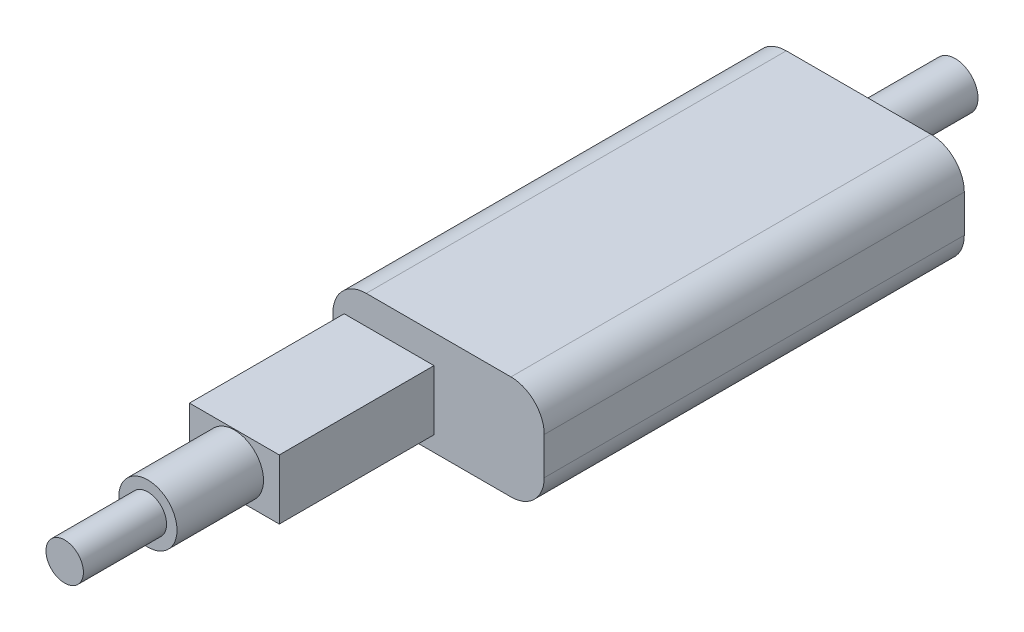
SolidWorks part; units mm, degrees
ref_plane "Plan de face" through (0, 0, 0) normal (0, 0, 1) x (1, 0, 0)
ref_plane "Plan de dessus" through (0, 0, 0) normal (0, 1, 0) x (1, 0, 0)
ref_plane "Plan de droite" through (0, 0, 0) normal (1, 0, 0) x (0, 0, -1)
sketch "Esquisse1" plane through (0, 0, 0) normal (0, 0, 1) x (1, 0, 0)
  line L1 (-12.7, 6.25) -> (12.7, 6.25)
  line L2 (-12.7, 6.25) -> (-12.7, -6.25)
  line L3 (-12.7, -6.25) -> (12.7, -6.25)
  line L4 (12.7, 6.25) -> (12.7, -6.25)
  point P4 (0, 6.25)
  point P6 (-12.7, 0)
  dimension "D1" = 25.4
  dimension "D2" = 12.5
extrude "Boss.-Extru.1" add sketch "Esquisse1" along normal mid plane 50.5
fillet "Congé1" radius 4 4 edges at (-12.7, -6.25, 0) (12.7, -6.25, 0) (12.7, 6.25, 0) (-12.7, 6.25, 0)
sketch "Esquisse2" plane through (0, 0, 25.25) normal (0, 0, 1) x (1, 0, 0)
  line L0 (-8.7, -6.25) -> (8.7, -6.25) construction
  line L1 (-7.9, 1.65) -> (-1, 1.65)
  line L2 (-7.9, 1.65) -> (-7.9, -0.25)
  line L3 (-7.9, -0.25) -> (-1, -0.25)
  line L4 (-1, 1.65) -> (-1, -0.25)
  line L5 (-12.7, 2.25) -> (-12.7, -2.25) construction
  dimension "D1" = 6.9
  dimension "D2" = 1.9
  dimension "D3" = 6
  dimension "D4" = 4.8
extrude "Boss.-Extru.2" add sketch "Esquisse2" along normal blind 1.5
sketch "Esquisse3" plane through (0, 0, 26.75) normal (0, 0, 1) x (1, 0, 0)
  line L0 (-1, 1.65) -> (-7.9, 1.65) construction
  line L1 (-9.85, 4.3) -> (0.95, 4.3)
  line L2 (-9.85, 4.3) -> (-9.85, -2.9)
  line L3 (-9.85, -2.9) -> (0.95, -2.9)
  line L4 (0.95, 4.3) -> (0.95, -2.9)
  line L5 (-7.9, 1.65) -> (-7.9, -0.25) construction
  point P6 (-4.45, 1.65)
  point P7 (-4.45, 4.3)
  point P10 (-7.9, 0.7)
  point P11 (-9.85, 0.7)
  dimension "D1" = 10.8
  dimension "D2" = 7.2
extrude "Boss.-Extru.3" add sketch "Esquisse3" along normal blind 18.6
sketch "Esquisse4" plane through (0, 0, 45.35) normal (0, 0, 1) x (1, 0, 0)
  line L0 (0.95, 4.3) -> (-9.85, 4.3) construction
  line L1 (-9.85, 4.3) -> (-9.85, -2.9) construction
  circle A0 centre (-4.45, 0.7) radius 3.5
  point P2 (0, 0)
  point P5 (-4.45, 4.3)
  point P8 (-9.85, 0.7)
  dimension "D1" = 7
extrude "Boss.-Extru.4" add sketch "Esquisse4" along normal blind 10.4
sketch "Esquisse5" plane through (0, 0, 55.75) normal (0, 0, 1) x (1, 0, 0)
  circle A0 centre (-4.45, 0.7) radius 2.25
  dimension "D1" = 4.5
extrude "Boss.-Extru.5" add sketch "Esquisse5" along normal blind 10
sketch "Esquisse7" plane through (0, 0, -25.25) normal (0, 0, -1) x (-1, 0, 0)
  line L0 (-8.7, 6.25) -> (8.7, 6.25) construction
  line L1 (-7.5, 3.75) -> (7.5, 3.75)
  line L2 (-7.5, 3.75) -> (-7.5, -1.85)
  line L3 (-7.5, -1.85) -> (7.5, -1.85)
  line L4 (7.5, 3.75) -> (7.5, -1.85)
  point P4 (0, -1.85)
  dimension "D1" = 5.6
  dimension "D2" = 15
  dimension "D3" = 2.5
extrude "Boss.-Extru.7" add sketch "Esquisse7" along normal blind 1.6
sketch "Esquisse6" plane through (0, 0, -26.85) normal (0, 0, -1) x (-1, 0, 0)
  line L0 (-8.7, 6.25) -> (8.7, 6.25) construction
  circle A0 centre (0, 1.25) radius 2.75
  dimension "D2" = 5.5
  dimension "D1" = 5
extrude "Boss.-Extru.6" add sketch "Esquisse6" along normal blind 10
